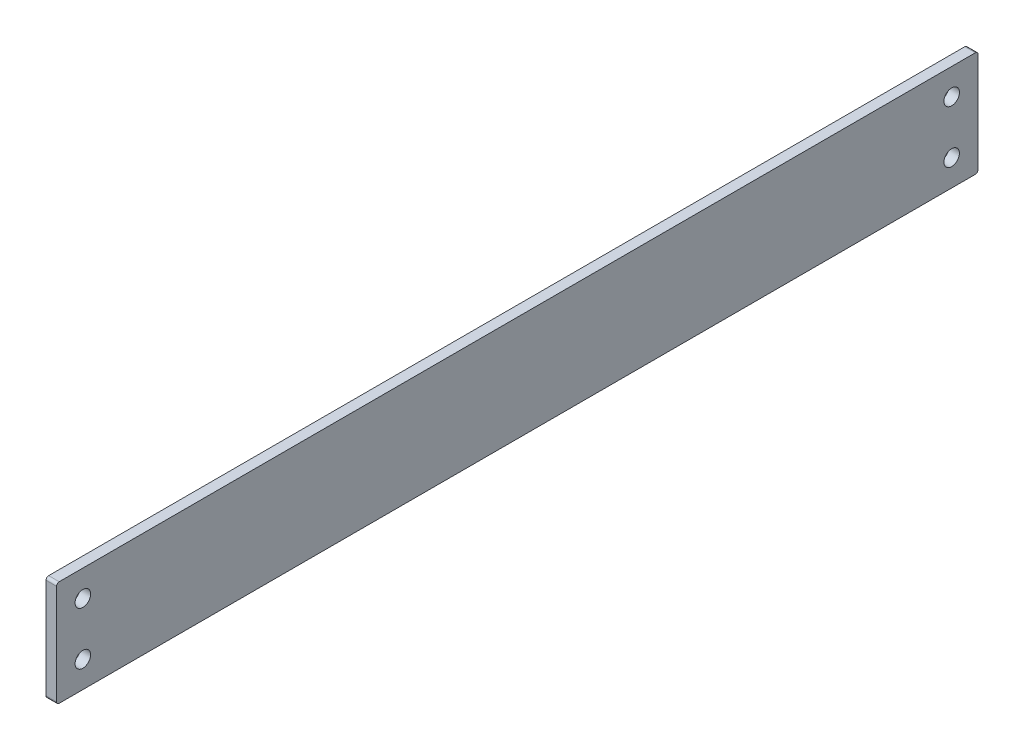
SolidWorks part; units mm, degrees
ref_plane "前视基准面" through (0, 0, 0) normal (0, 0, 1) x (1, 0, 0)
ref_plane "上视基准面" through (0, 0, 0) normal (0, 1, 0) x (1, 0, 0)
ref_plane "右视基准面" through (0, 0, 0) normal (1, 0, 0) x (0, 0, -1)
sketch "草图1" plane through (0, 0, 0) normal (1, 0, 0) x (0, 0, -1)
  line L0 (175, 40) -> (175, 0) construction
  line L1 (0, 0) -> (350, 0)
  line L2 (0, 0) -> (0, 40)
  line L3 (0, 40) -> (350, 40)
  line L4 (350, 0) -> (350, 40)
  circle A0 centre (10, 30) radius 2.95
  circle A1 centre (10, 10) radius 2.95
  circle A10 centre (340, 10) radius 2.95
  circle A11 centre (340, 30) radius 2.95
  dimension "D6" = 5.9
  dimension "D1" = 350
  dimension "D2" = 40
  dimension "D3" = 10
  dimension "D4" = 20
  dimension "D5" = 10
extrude "凸台-拉伸1" add sketch "草图1" along normal blind 4
fillet "圆角1" radius 1 4 edges at (2, 0, -350) (2, 40, -350) (2, 0, 0) (2, 40, 0)
